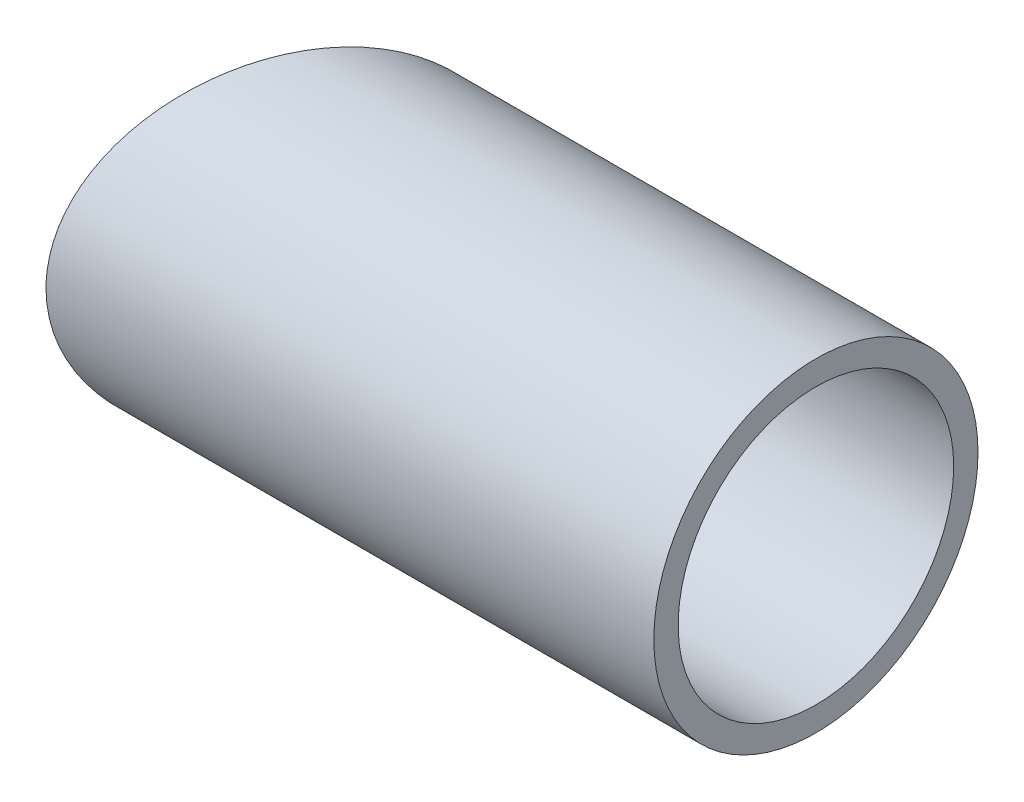
SolidWorks part; units mm, degrees
material "ASTM A36 Steel"
ref_plane "Front Plane" through (0, 0, 0) normal (0, 0, 1) x (1, 0, 0)
ref_plane "Top Plane" through (0, 0, 0) normal (0, 1, 0) x (1, 0, 0)
ref_plane "Right Plane" through (0, 0, 0) normal (1, 0, 0) x (0, 0, -1)
sketch "Sketch1" plane through (0, 0, 0) normal (1, 0, 0) x (0, 0, -1)
  circle A0 centre (0, 0) radius 20
  dimension "D1" = 40
extrude "Boss-Extrude1" add sketch "Sketch1" along normal blind 75
sketch "Sketch3" plane through (75, 0, 0) normal (1, 0, 0) x (0, 0, -1)
  circle A0 centre (0, 0) radius 14.5
  dimension "D1" = 29
extrude "Cut-Extrude2" cut sketch "Sketch3" against normal through all both and the other way through all
sketch "Sketch4" plane through (75, 0, 0) normal (1, 0, 0) x (0, 0, -1)
  circle A0 centre (0, 0) radius 17
  dimension "D1" = 34
extrude "Cut-Extrude3" cut sketch "Sketch4" against normal blind 25
ref_plane "Plane1" through (0, 20, 0) normal (0, 1, 0) x (1, 0, 0)
sketch "Sketch5" plane through (0, 0, 0) normal (0, 1, 0) x (1, 0, 0)
  circle A0 centre (-445.1306, 211) radius 501.5
  dimension "D1" = 1003
  dimension "D2" = 211
extrude "Cut-Extrude4" cut sketch "Sketch5" against normal through all both and the other way through all
